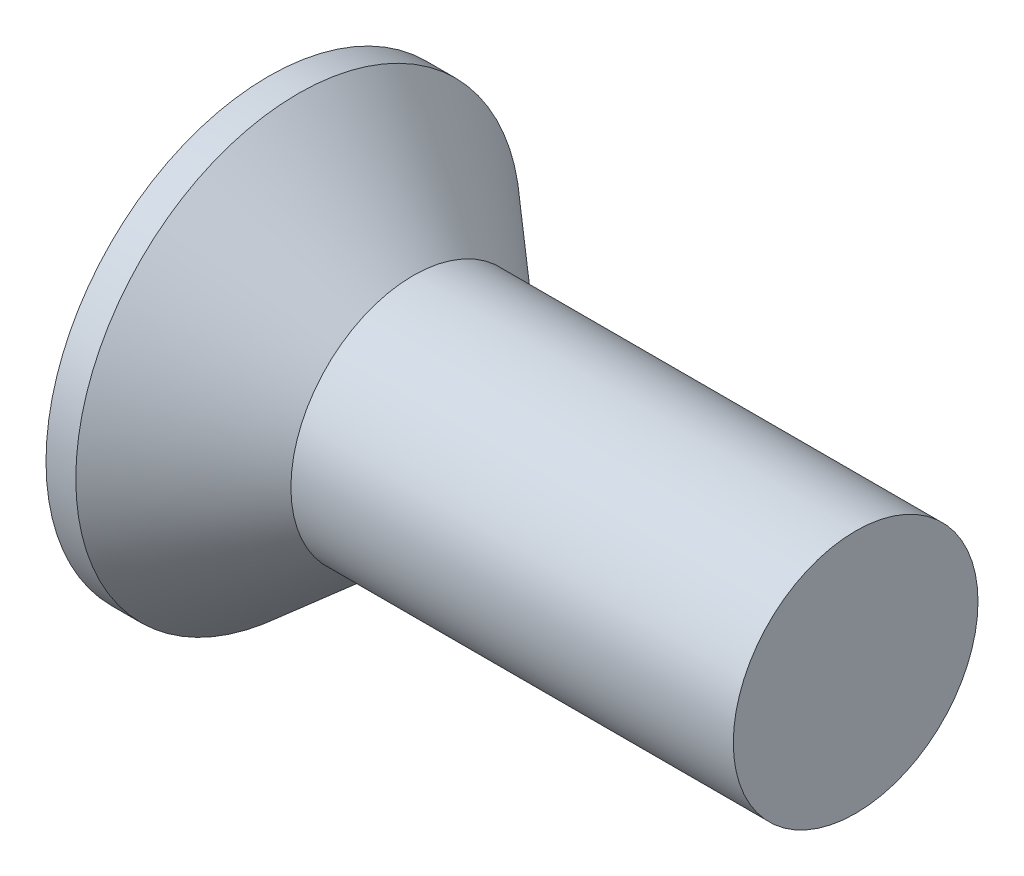
SolidWorks part; units mm, degrees
ref_plane "Plane1" through (0, 0, 0) normal (0, 0, 1) x (1, 0, 0)
ref_plane "Plane2" through (0, 0, 0) normal (0, 1, 0) x (1, 0, 0)
ref_plane "Plane3" through (0, 0, 0) normal (1, 0, 0) x (0, 0, -1)
sketch "BodySke" plane through (0, 0, 0) normal (0, 0, 1) x (1, 0, 0)
  line L0 (0, 0) -> (0, 7.2136)
  line L1 (0, 7.2136) -> (0.9662, 7.2136)
  line L2 (4.699, 3.9688) -> (19.05, 3.9688)
  line L3 (19.05, 3.9688) -> (19.05, 0)
  line L4 (19.05, 0) -> (0, 0)
  line L5 (-6.35, 0) -> (82.55, 0) construction
  line L6 (4.699, -3.9688) -> (19.05, -3.9688) construction
  line L7 (0.9662, -7.2136) -> (4.699, -3.9688) construction
  line L8 (0.9662, 7.2136) -> (4.699, 3.9688)
  line L9 (0, -7.2136) -> (0.9662, -7.2136) construction
  line L10 (6.1087, 5.5562) -> (6.1087, -3.9687) construction
  line L11 (0, 6.35) -> (0, -3.175) construction
  dimension "Diameter" = 7.9375
  dimension "Length" = 19.05
  dimension "Head_ht" = 4.699
  dimension "Head_dia" = 14.4272
  dimension "Head_ang" = 82
  dimension "D6" = 0.9662
  dimension "Advance" = 1.4097
  dimension "Thread_nom" = 19.05
revolve "Base-Revolve" add sketch "BodySke" angle 360 about L5
cosmetic thread "ThreadCosmetic" [suppressed] parameters "Thread_length"=12.9413, "Thread_minor"=6.2586
sketch "Sketch2" plane through (0, 0, 0) normal (-1, 0, 0) x (0, 0, 1)
  line L0 (-7.2136, -1.0668) -> (7.2136, -1.0668)
  line L1 (-7.2136, -1.0668) -> (-7.2136, 1.0668)
  line L2 (7.2136, 1.0668) -> (-7.2136, 1.0668)
  line L3 (7.2136, 1.0668) -> (7.2136, -1.0668)
  dimension "D1" = 1.0668
  dimension "Slot_width" = 2.1336
  dimension "D2" = 14.4272
  dimension "D3" = 7.2136
extrude "Slot" [suppressed] cut sketch "Sketch2" against normal blind 2.2352
sketch "Sketch3" plane through (0, 0, 0) normal (-1, 0, 0) x (0, 0, 1)
  line L0 (-0.9398, 5.6388) -> (0.9398, 5.6388)
  line L1 (0.9398, 5.6388) -> (0.9398, -5.6388)
  line L2 (0.9398, -5.6388) -> (-0.9398, -5.6388)
  line L3 (-0.9398, -5.6388) -> (-0.9398, 5.6388)
  dimension "D1" = 5.6388
  dimension "Cross_dia" = 11.2776
  dimension "D2" = 0.9398
  dimension "Cross_width" = 1.8796
ref_plane "Plane4" through (6.6548, 0, 0) normal (-1, 0, 0) x (0, 0, 1)
sketch "Sketch4" plane through (6.6548, 0, 0) normal (-1, 0, 0) x (0, 0, 1)
  line L0 (-0.4699, 0.4699) -> (0.4699, 0.4699)
  line L3 (0.4699, 0.4699) -> (0.4699, -0.4699)
  line L4 (0.4699, -0.4699) -> (-0.4699, -0.4699)
  line L5 (-0.4699, -0.4699) -> (-0.4699, 0.4699)
  dimension "D1" = 0.9398
  dimension "D2" = 0.9398
  dimension "D3" = 0.4699
  dimension "D4" = 0.4699
loft "Cross" cut profiles "Sketch3", "Sketch4"
pattern_circular "CirPattern1" count 2 every 90 about axis through (0, 0, 0) along (1, 0, 0) of "Cross"
sketch "ThdSchSke" plane through (0, 0, 0) normal (0, 0, 1) x (1, 0, 0)
  line L0 (6.1087, -3.1293) -> (5.5209, -3.9688)
  line L1 (6.1087, -3.1293) -> (6.6965, -3.9688)
  line L2 (6.6965, -3.9688) -> (6.6965, -4.9609)
  line L3 (-3.175, 0) -> (5.1513, 0) construction
  line L5 (6.6965, -4.9609) -> (5.5209, -4.9609)
  line L6 (5.5209, -4.9609) -> (5.5209, -3.9688)
  line L7 (0, 7.2136) -> (0, -7.2136) construction
  dimension "Thread_minor" = 6.2586
  dimension "Diameter" = 7.9375
  dimension "Start" = 6.1087
  dimension "SideAngle" = 55
  dimension "VeeAngle" = 70
  dimension "Overcut" = 9.9219
revolve "ThreadSchematic" [suppressed] cut sketch "ThdSchSke" angle 360 about L3
pattern_linear "ThdSchPat" [suppressed]
equation "\"D1@Sketch3\" = \"Cross_dia@Sketch3\" / 2"
equation "\"D2@Sketch3\" = \"Cross_width@Sketch3\" / 2"
equation "\"D1@Sketch4\" = \"Cross_width@Sketch3\" *.5"
equation "\"D2@Sketch4\" = \"D1@Sketch4\""
equation "\"D4@Sketch4\" = \"D2@Sketch4\" / 2"
equation "\"D3@Sketch4\" = \"D1@Sketch4\" / 2"
equation "\"D1@Sketch2\" = \"Slot_width@Sketch2\" / 2"
equation "\"D2@Sketch2\" = \"Head_dia@BodySke\""
equation "\"D3@Sketch2\" = \"D2@Sketch2\" / 2"
equation "\"Thread_length@ThreadCosmetic\" = ((sgn( (\"Length@BodySke\" - \"Advance@BodySke\" - \"Head_ht@BodySke\" ) - \"Thread_nom@BodySke\" )-1)*( (\"Length@BodySke\" - \"Advance@BodySke\" - \"Head_ht@BodySke\" ) - \"Thread_nom@BodySke\" ))/-2+ \"Thread_nom@BodySke\""
equation "\"Thread_minor@ThdSchSke\" = \"Thread_minor@ThreadCosmetic\""
equation "\"Diameter@ThdSchSke\" = \"Diameter@BodySke\""
equation "\"Overcut@ThdSchSke\" = \"Diameter@BodySke\" * 1.25"
equation "\"Start@ThdSchSke\" = 0.000001 + \"Length@BodySke\" - \"Thread_length@ThreadCosmetic\"  '---Countersunk---"
equation "\"Num_threads@ThdSchPat\" = int( \"Thread_length@ThreadCosmetic\" / \"Advance@BodySke\" + 0.999 )  + 1"
equation "\"Advance@ThdSchPat\" = \"Thread_length@ThreadCosmetic\" /  (\"Num_threads@ThdSchPat\" - 1) 'relax it"
